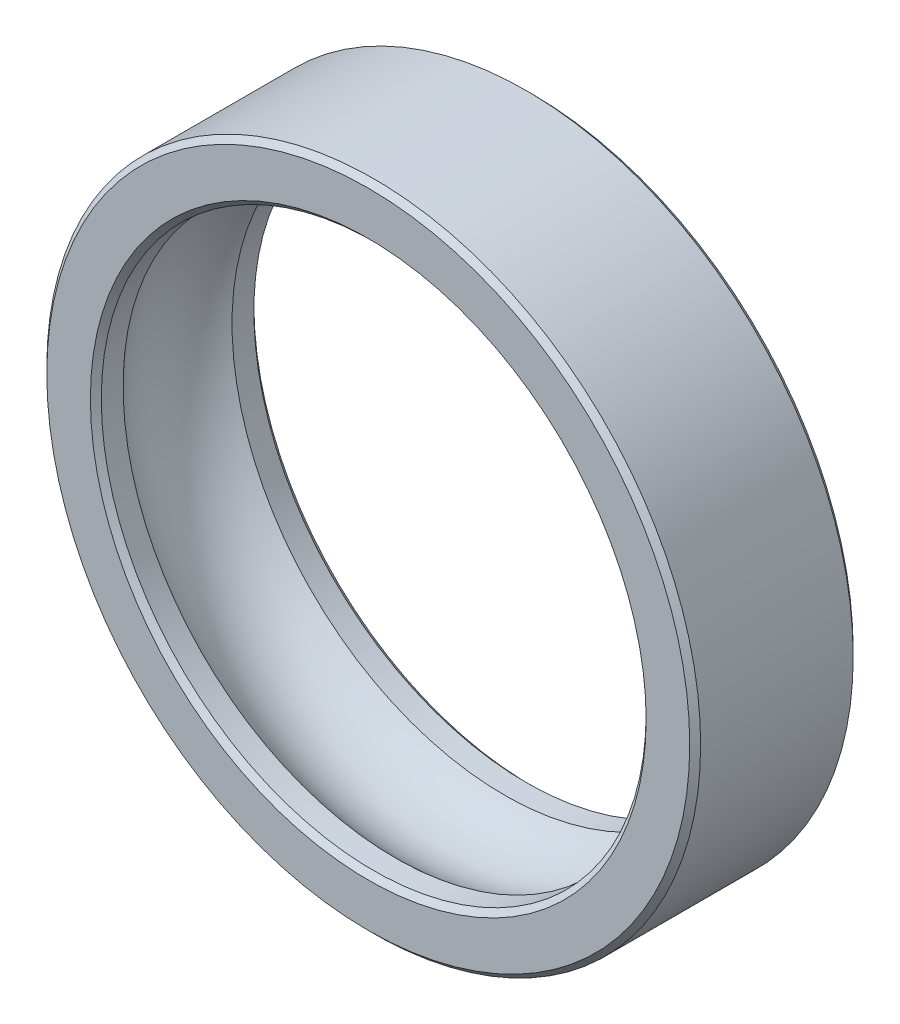
SolidWorks part; units mm, degrees
ref_plane "Front Plane" through (0, 0, 0) normal (0, 0, 1) x (1, 0, 0)
ref_plane "Top Plane" through (0, 0, 0) normal (0, 1, 0) x (1, 0, 0)
ref_plane "Right Plane" through (0, 0, 0) normal (1, 0, 0) x (0, 0, -1)
sketch "Sketch1" plane through (0, 0, 0) normal (1, 0, 0) x (0, 0, -1)
  line L0 (0, 0) -> (482.2864, 0) construction
  line L1 (-381, 1524) -> (381, 1524)
  line L2 (381, 1524) -> (381, 1270)
  line L3 (381, 1270) -> (254, 1270)
  line L4 (-381, 1270) -> (-254, 1270)
  line L5 (-381, 1524) -> (-381, 1270)
  arc A0 (-254, 1270) -> (254, 1270) centre (0, 1016) cw
  point P6 (0, 1524)
revolve "Revolve1" add sketch "Sketch1" angle 360 about L0
chamfer "Chamfer1" distance 25.4 angle 45 4 edges at (1524, 0, 381) (1524, 0, -381) (1270, 0, 381) (1270, 0, -381)
